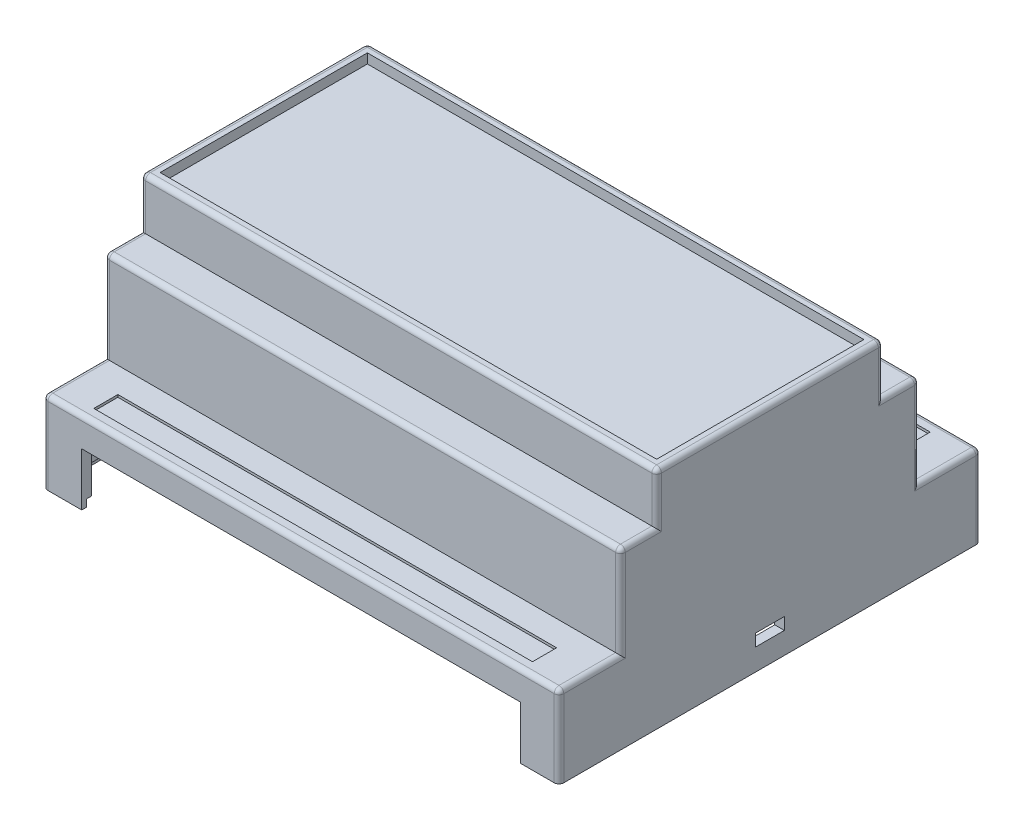
SolidWorks part; units mm, degrees
ref_plane "Front Plane" through (0, 0, 0) normal (0, 0, 1) x (1, 0, 0)
ref_plane "Top Plane" through (0, 0, 0) normal (0, 1, 0) x (1, 0, 0)
ref_plane "Right Plane" through (0, 0, 0) normal (1, 0, 0) x (0, 0, -1)
sketch "Sketch1" plane through (0, 0, 0) normal (1, 0, 0) x (0, 0, -1)
  line L12 (-43.75, -23.25) -> (43.75, -23.25)
  line L13 (43.75, -23.25) -> (43.75, -6.25)
  line L14 (43.75, -6.25) -> (31, -6.25)
  line L15 (31, -6.25) -> (31, 12.75)
  line L16 (31, 12.75) -> (23.5, 12.75)
  line L17 (23.5, 12.75) -> (23.5, 23.25)
  line L18 (23.5, 23.25) -> (-23.5, 23.25)
  line L19 (-23.5, 23.25) -> (-23.5, 12.75)
  line L20 (-23.5, 12.75) -> (-31, 12.75)
  line L21 (-31, 12.75) -> (-31, -6.25)
  line L22 (-31, -6.25) -> (-43.75, -6.25)
  line L23 (-43.75, -6.25) -> (-43.75, -23.25)
extrude "Boss-Extrude1" add sketch "Sketch1" against normal blind 2
sketch "Sketch2" plane through (-2, 0, 0) normal (-1, 0, 0) x (0, 0, 1)
  line L0 (-43.75, -23.25) -> (-43.75, -6.25) construction
  line L1 (-43.75, -23.25) -> (-43.75, -6.25)
  line L2 (-43.75, -6.25) -> (-31, -6.25) construction
  line L3 (-43.75, -6.25) -> (-31, -6.25)
  line L4 (-31, -6.25) -> (-31, 12.75) construction
  line L5 (-31, -6.25) -> (-31, 12.75)
  line L6 (-31, 12.75) -> (-23.5, 12.75) construction
  line L7 (-31, 12.75) -> (-23.5, 12.75)
  line L8 (-43.75, -23.25) -> (-41.75, -23.25)
  line L9 (43.75, -23.25) -> (-43.75, -23.25) construction
  line L10 (-41.75, -23.25) -> (-41.75, -7.25)
  line L11 (-41.75, -7.25) -> (-28.5, -7.25)
  line L12 (-28.5, -7.25) -> (-28.5, 11.75)
  line L13 (-28.5, 11.75) -> (-22.5, 11.75)
  line L14 (-22.5, 11.75) -> (-22.5, 19.75)
  line L15 (-23.5, 12.75) -> (-23.5, 23.25) construction
  line L16 (-23.5, 23.25) -> (23.5, 23.25) construction
  line L17 (-23.5, 12.75) -> (-23.5, 23.25)
  line L18 (-23.5, 23.25) -> (23.5, 23.25)
  line L19 (23.5, 23.25) -> (23.5, 12.75)
  line L20 (23.5, 12.75) -> (31, 12.75)
  line L21 (23.5, 12.75) -> (31, 12.75) construction
  line L22 (31, 12.75) -> (31, -6.25)
  line L23 (31, -6.25) -> (43.75, -6.25)
  line L24 (43.75, -6.25) -> (43.75, -23.25)
  line L25 (43.75, -23.25) -> (41.75, -23.25)
  line L26 (41.75, -23.25) -> (41.75, -7.25)
  line L27 (41.75, -7.25) -> (28.5, -7.25)
  line L28 (28.5, -7.25) -> (28.5, 11.75)
  line L29 (28.5, 11.75) -> (22.5, 11.75)
  line L30 (22.5, 11.75) -> (22.5, 19.75)
  line L31 (22.5, 19.75) -> (-22.5, 19.75)
  dimension "D1" = 2
  dimension "D2" = 1
  dimension "D3" = 2.5
  dimension "D4" = 1
  dimension "D5" = 1
  dimension "D6" = 3.5
  dimension "D7" = 2
  dimension "D8" = 1
  dimension "D9" = 2.5
  dimension "D10" = 1
  dimension "D11" = 1
extrude "Boss-Extrude2" add sketch "Sketch2" along normal blind 103
sketch "Sketch3" plane through (-105, 0, 0) normal (-1, 0, 0) x (0, 0, 1)
  line L12 (43.75, -23.25) -> (43.75, -6.25)
  line L13 (-43.75, -23.25) -> (43.75, -23.25)
  line L14 (-43.75, -6.25) -> (-43.75, -23.25)
  line L15 (-31, -6.25) -> (-43.75, -6.25)
  line L16 (-31, 12.75) -> (-31, -6.25)
  line L17 (-23.5, 12.75) -> (-31, 12.75)
  line L18 (-23.5, 23.25) -> (-23.5, 12.75)
  line L19 (23.5, 23.25) -> (-23.5, 23.25)
  line L20 (23.5, 12.75) -> (23.5, 23.25)
  line L21 (31, 12.75) -> (23.5, 12.75)
  line L22 (31, -6.25) -> (31, 12.75)
  line L23 (43.75, -6.25) -> (31, -6.25)
  line L24 (43.75, -23.25) -> (43.75, -6.25)
  line L25 (-43.75, -23.25) -> (43.75, -23.25)
  line L26 (-43.75, -6.25) -> (-43.75, -23.25)
  line L27 (-31, -6.25) -> (-43.75, -6.25)
  line L28 (-31, 12.75) -> (-31, -6.25)
  line L29 (-23.5, 12.75) -> (-31, 12.75)
  line L30 (-23.5, 23.25) -> (-23.5, 12.75)
  line L31 (23.5, 23.25) -> (-23.5, 23.25)
  line L32 (23.5, 12.75) -> (23.5, 23.25)
  line L33 (31, 12.75) -> (23.5, 12.75)
  line L34 (31, -6.25) -> (31, 12.75)
  line L35 (43.75, -6.25) -> (31, -6.25)
  dimension "D1" = 0
extrude "Boss-Extrude3" add sketch "Sketch3" along normal blind 2
sketch "Sketch4" plane through (0, 23.25, 0) normal (0, 1, 0) x (1, 0, 0)
  line L0 (-107, 23.5) -> (0, 23.5) construction
  line L1 (-105, -21.5) -> (-2, -21.5)
  line L2 (-105, -21.5) -> (-105, 21.5)
  line L3 (-105, 21.5) -> (-2, 21.5)
  line L4 (-2, -21.5) -> (-2, 21.5)
  line L5 (-107, -23.5) -> (-107, 23.5) construction
  line L6 (-107, -23.5) -> (0, -23.5) construction
  line L7 (0, 23.5) -> (0, -23.5) construction
  dimension "D1" = 2
  dimension "D2" = 2
  dimension "D3" = 2
  dimension "D4" = 2
extrude "Cut-Extrude1" cut sketch "Sketch4" against normal blind 2
sketch "Sketch5" plane through (0, -6.25, 0) normal (0, 1, 0) x (1, 0, 0)
  line L0 (-107, -43.75) -> (0, -43.75) construction
  line L1 (-99, -41.25) -> (-8, -41.25)
  line L2 (-99, -41.25) -> (-99, -36.25)
  line L3 (-99, -36.25) -> (-8, -36.25)
  line L4 (-8, -41.25) -> (-8, -36.25)
  line L5 (-99, 36.25) -> (-8, 36.25)
  line L6 (-99, 36.25) -> (-99, 41.25)
  line L7 (-99, 41.25) -> (-8, 41.25)
  line L8 (-8, 36.25) -> (-8, 41.25)
  line L9 (-107, 43.75) -> (0, 43.75) construction
  line L10 (-107, -43.75) -> (-107, -31) construction
  line L12 (-107, 31) -> (-107, 43.75) construction
  dimension "D1" = 5
  dimension "D2" = 91
  dimension "D3" = 5
  dimension "D4" = 2.5
  dimension "D5" = 2.5
  dimension "D6" = 8
  dimension "D7" = 8
extrude "Cut-Extrude2" cut sketch "Sketch5" against normal blind 0.5
sketch "Sketch7" plane through (0, -23.25, 0) normal (0, -1, 0) x (1, 0, 0)
  line L1 (-105, -41.75) -> (-2, -41.75)
  line L2 (-105, -41.75) -> (-105, 41.75)
  line L3 (-105, 41.75) -> (-2, 41.75)
  line L4 (-2, -41.75) -> (-2, 41.75)
  line L5 (-106, -42.75) -> (-1, -42.75)
  line L6 (-106, -42.75) -> (-106, 42.75)
  line L7 (-106, 42.75) -> (-1, 42.75)
  line L8 (-1, -42.75) -> (-1, 42.75)
  dimension "D1" = 1
  dimension "D2" = 1
  dimension "D3" = 1
  dimension "D4" = 1
extrude "Cut-Extrude3" cut sketch "Sketch7" against normal blind 1.5
sketch "Sketch8" plane through (0, 0, 43.75) normal (0, 0, 1) x (1, 0, 0)
  line L0 (-107, -23.25) -> (0, -23.25) construction
  line L1 (-99, -23.25) -> (-8, -23.25)
  line L2 (-99, -23.25) -> (-99, -12.25)
  line L3 (-99, -12.25) -> (-8, -12.25)
  line L4 (-8, -23.25) -> (-8, -12.25)
  line L5 (-107, -23.25) -> (-107, -6.25) construction
  line L6 (0, -6.25) -> (0, -23.25) construction
  line L7 (-107, -6.25) -> (0, -6.25) construction
  dimension "D1" = 8
  dimension "D2" = 8
  dimension "D3" = 6
extrude "Cut-Extrude4" cut sketch "Sketch8" against normal up to surface (87.5 mm away) up to face at (-53.5, -14.75, -43.75)
sketch "Sketch9" plane through (0, 0, 0) normal (1, 0, 0) x (0, 0, -1)
  line L0 (-43.75, -6.25) -> (-43.75, -23.25) construction
  line L1 (-3, -18.75) -> (3, -18.75)
  line L2 (-3, -18.75) -> (-3, -16.25)
  line L3 (-3, -16.25) -> (3, -16.25)
  line L4 (3, -18.75) -> (3, -16.25)
  line L6 (-43.75, -23.25) -> (43.75, -23.25) construction
  dimension "D1" = 6
  dimension "D2" = 2.5
  dimension "D3" = 40.75
  dimension "D4" = 4.5
extrude "Cut-Extrude5" cut sketch "Sketch9" against normal up to surface (107 mm away) up to face at (-107, 2.1667, 0)
fillet "Fillet1" radius 1 28 edges at (0, -14.75, -43.75) (-107, -14.75, -43.75) (-107, -14.75, 43.75) (0, -14.75, 43.75) (0, -6.25, 37.375) (0, 3.25, 31) (0, 18, 23.5) (0, 12.75, 27.25) (-53.5, 12.75, 31) (-53.5, -6.25, 43.75) (-107, -6.25, 37.375) (-107, 3.25, 31) (-107, 12.75, 27.25) (-107, 18, 23.5) (-53.5, 23.25, 23.5) (-107, 23.25, 0) (-107, 18, -23.5) (-107, 12.75, -27.25) (-107, 3.25, -31) (-107, -6.25, -37.375) (-53.5, 12.75, -31) (-53.5, 23.25, -23.5) (0, 23.25, 0) (0, 18, -23.5) (0, 12.75, -27.25) (0, 3.25, -31) (0, -6.25, -37.375) (-53.5, -6.25, -43.75)
